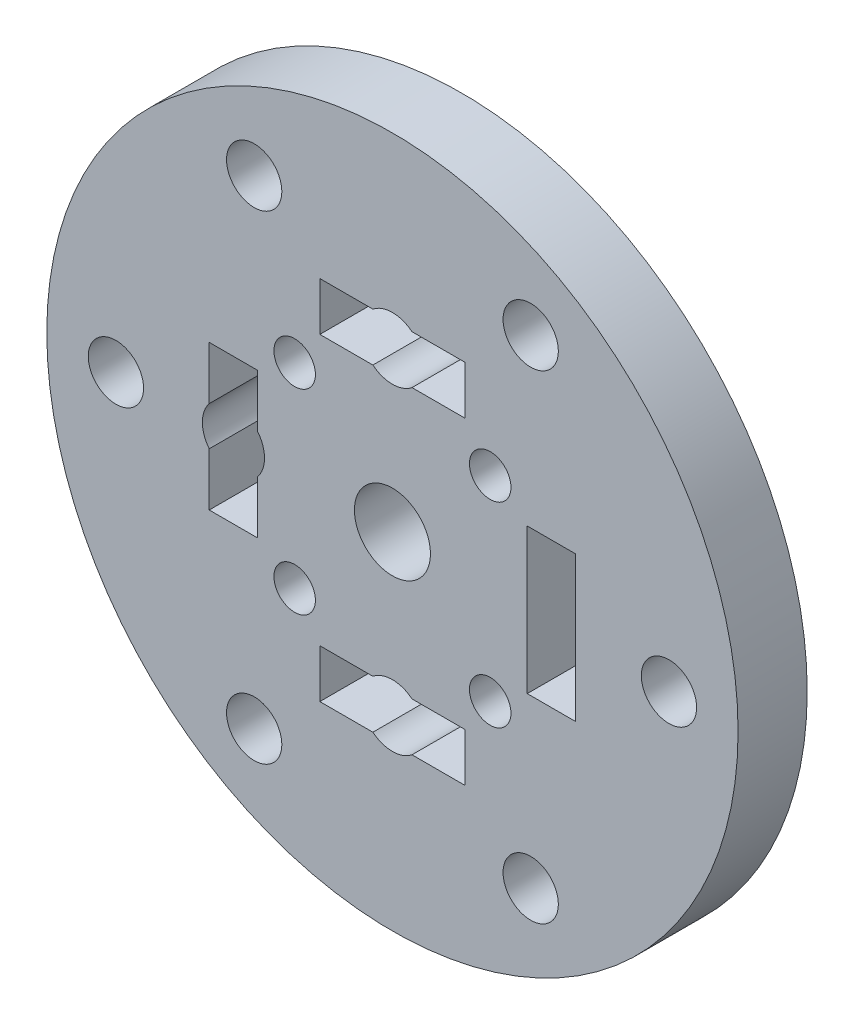
SolidWorks part; units mm, degrees
ref_plane "前视基准面" through (0, 0, 0) normal (0, 0, 1) x (1, 0, 0)
ref_plane "上视基准面" through (0, 0, 0) normal (0, 1, 0) x (1, 0, 0)
ref_plane "右视基准面" through (0, 0, 0) normal (1, 0, 0) x (0, 0, -1)
sketch "草图1" plane through (0, 0, 0) normal (0, 0, 1) x (1, 0, 0)
  line L1 (7.0711, 7.0711) -> (0, 0) construction
  line L2 (-1000, 0) -> (49000, 0) construction
  line L3 (5, -10) -> (-5, -10)
  line L4 (10, 5) -> (13, 5)
  line L5 (10, 5) -> (10, -5)
  line L6 (10, -5) -> (13, -5)
  line L7 (13, 5) -> (13, -5)
  line L8 (10, 5) -> (13, -5) construction
  line L9 (10, -5) -> (13, 5) construction
  line L10 (5, -10) -> (5, -13)
  line L11 (5, -13) -> (-5, -13)
  line L12 (-5, -10) -> (-5, -13)
  line L13 (-10, -5) -> (-10, 5)
  line L14 (-10, -5) -> (-13, -5)
  line L15 (-13, -5) -> (-13, 5)
  line L16 (-10, 5) -> (-13, 5)
  line L17 (-5, 10) -> (5, 10)
  line L18 (-5, 10) -> (-5, 13)
  line L19 (-5, 13) -> (5, 13)
  line L20 (5, 10) -> (5, 13)
  circle A0 centre (0, 0) radius 25
  circle A2 centre (7.0711, 7.0711) radius 1.5
  circle A3 centre (11.5, 0) radius 2 construction
  circle A4 centre (7.0711, -7.0711) radius 1.5
  circle A5 centre (0, -11.5) radius 2
  circle A6 centre (-7.0711, -7.0711) radius 1.5
  circle A8 centre (-7.0711, 7.0711) radius 1.5
  circle A9 centre (0, 11.5) radius 2
  circle A10 centre (-11.5, 0) radius 2 [skipped]
  circle A11 centre (-11.5, 0) radius 2
  circle A12 centre (-20, 0) radius 2
  circle A13 centre (-10, 17.3205) radius 2
  circle A14 centre (10, 17.3205) radius 2
  circle A15 centre (20, 0) radius 2
  circle A16 centre (10, -17.3205) radius 2
  circle A17 centre (-10, -17.3205) radius 2
  circle A18 centre (0, 0) radius 2.75
  point P3 (-11.5, 0)
  point P8 (11.5, 0)
  point P17 (-11.5, 5)
  point P44 (0, 0)
  point P60 (0, 0)
  dimension "D1" = 50
  dimension "D2" = 5.5
  dimension "D4" = 3
  dimension "D9" = 4
  dimension "D12" = 4
  dimension "D13" = 4
  dimension "D3" = 20
  dimension "D5" = 45
  dimension "D6" = 10
  dimension "D7" = 10
  dimension "D8" = 3
  dimension "D10" = 10
  dimension "D11" = 4
  dimension "D15" = 6
extrude "凸台-拉伸1" add sketch "草图1" along normal blind 5
sketch "草图3" plane through (0, 0, 5) normal (0, 0, 1) x (1, 0, 0)
  line L0 (10, -5) -> (13, -5) construction
  line L1 (13, 5) -> (13, -5) construction
  line L2 (10, 5) -> (13, 5) construction
  line L3 (10, 5) -> (10, -5) construction
  line L4 (-5, 10) -> (-5, 13) construction
  line L5 (-5, 13) -> (-1.3229, 13) construction
  line L6 (-5, 10) -> (-1.3229, 10) construction
  line L7 (1.3229, 13) -> (5, 13) construction
  line L8 (5, 10) -> (5, 13) construction
  line L9 (1.3229, 10) -> (5, 10) construction
  line L10 (5, -10) -> (1.3229, -10) construction
  line L11 (5, -10) -> (5, -13) construction
  line L12 (5, -13) -> (1.3229, -13) construction
  line L13 (-1.3229, -13) -> (-5, -13) construction
  line L14 (-5, -10) -> (-5, -13) construction
  line L15 (-1.3229, -10) -> (-5, -10) construction
  line L16 (-13, -5) -> (-13, -1.3229) construction
  line L17 (-13, 1.3229) -> (-13, 5) construction
  line L18 (-10, 5) -> (-13, 5) construction
  line L19 (-10, 1.3229) -> (-10, 5) construction
  line L20 (-10, -5) -> (-10, -1.3229) construction
  line L21 (-10, -5) -> (-13, -5) construction
  line L22 (10, -5) -> (13, -5)
  line L23 (13, 5) -> (13, -5)
  line L24 (10, 5) -> (13, 5)
  line L25 (10, 5) -> (10, -5)
  line L26 (-5, 10) -> (-5, 13)
  line L27 (-5, 13) -> (-1.3229, 13)
  line L28 (-5, 10) -> (-1.3229, 10)
  line L29 (1.3229, 13) -> (5, 13)
  line L30 (5, 10) -> (5, 13)
  line L31 (1.3229, 10) -> (5, 10)
  line L32 (5, -10) -> (1.3229, -10)
  line L33 (5, -10) -> (5, -13)
  line L34 (5, -13) -> (1.3229, -13)
  line L35 (-1.3229, -13) -> (-5, -13)
  line L36 (-5, -10) -> (-5, -13)
  line L37 (-1.3229, -10) -> (-5, -10)
  line L38 (-13, -5) -> (-13, -1.3229)
  line L39 (-13, 1.3229) -> (-13, 5)
  line L40 (-10, 5) -> (-13, 5)
  line L41 (-10, 1.3229) -> (-10, 5)
  line L42 (-10, -5) -> (-10, -1.3229)
  line L43 (-10, -5) -> (-13, -5)
  line L44 (-5.25, 9.75) -> (-5.25, 13.25)
  line L45 (-5.25, 13.25) -> (-1.4142, 13.25)
  line L46 (1.4142, 13.25) -> (5.25, 13.25)
  line L47 (5.25, 9.75) -> (5.25, 13.25)
  line L48 (1.4142, 9.75) -> (5.25, 9.75)
  line L49 (-5.25, 9.75) -> (-1.4142, 9.75)
  line L50 (-13.25, -5.25) -> (-13.25, -1.4142)
  line L51 (-13.25, 1.4142) -> (-13.25, 5.25)
  line L52 (-9.75, 5.25) -> (-13.25, 5.25)
  line L53 (-9.75, 1.4142) -> (-9.75, 5.25)
  line L54 (-9.75, -5.25) -> (-9.75, -1.4142)
  line L55 (-9.75, -5.25) -> (-13.25, -5.25)
  line L56 (5.25, -9.75) -> (1.4142, -9.75)
  line L57 (-1.4142, -9.75) -> (-5.25, -9.75)
  line L58 (-5.25, -9.75) -> (-5.25, -13.25)
  line L59 (-1.4142, -13.25) -> (-5.25, -13.25)
  line L60 (5.25, -13.25) -> (1.4142, -13.25)
  line L61 (5.25, -9.75) -> (5.25, -13.25)
  line L62 (9.75, -5.25) -> (13.25, -5.25)
  line L63 (13.25, 5.25) -> (13.25, -5.25)
  line L64 (9.75, 5.25) -> (13.25, 5.25)
  line L65 (9.75, 5.25) -> (9.75, -5.25)
  arc A0 (-1.3229, 10) -> (1.3229, 10) centre (0, 11.5) ccw construction
  arc A1 (1.3229, 13) -> (-1.3229, 13) centre (0, 11.5) ccw construction
  arc A2 (-1.3229, -13) -> (1.3229, -13) centre (0, -11.5) ccw construction
  arc A3 (1.3229, -10) -> (-1.3229, -10) centre (0, -11.5) ccw construction
  arc A4 (-13, 1.3229) -> (-13, -1.3229) centre (-11.5, 0) ccw construction
  arc A5 (-10, -1.3229) -> (-10, 1.3229) centre (-11.5, 0) ccw construction
  arc A6 (-1.3229, 10) -> (1.3229, 10) centre (0, 11.5) ccw
  arc A7 (1.3229, 13) -> (-1.3229, 13) centre (0, 11.5) ccw
  arc A8 (-1.3229, -13) -> (1.3229, -13) centre (0, -11.5) ccw
  arc A9 (1.3229, -10) -> (-1.3229, -10) centre (0, -11.5) ccw
  arc A10 (-13, 1.3229) -> (-13, -1.3229) centre (-11.5, 0) ccw
  arc A11 (-10, -1.3229) -> (-10, 1.3229) centre (-11.5, 0) ccw
  arc A12 (1.4142, 13.25) -> (-1.4142, 13.25) centre (0, 11.5) ccw
  arc A13 (-1.4142, 9.75) -> (1.4142, 9.75) centre (0, 11.5) ccw
  arc A14 (-13.25, 1.4142) -> (-13.25, -1.4142) centre (-11.5, 0) ccw
  arc A15 (-9.75, -1.4142) -> (-9.75, 1.4142) centre (-11.5, 0) ccw
  arc A16 (1.4142, -9.75) -> (-1.4142, -9.75) centre (0, -11.5) ccw
  arc A17 (-1.4142, -13.25) -> (1.4142, -13.25) centre (0, -11.5) ccw
  dimension "D1" = 0.25
  dimension "D2" = 0.25
  dimension "D3" = 0.25
  dimension "D4" = 0.25
extrude "切除-拉伸1" cut sketch "草图3" against normal blind 10
